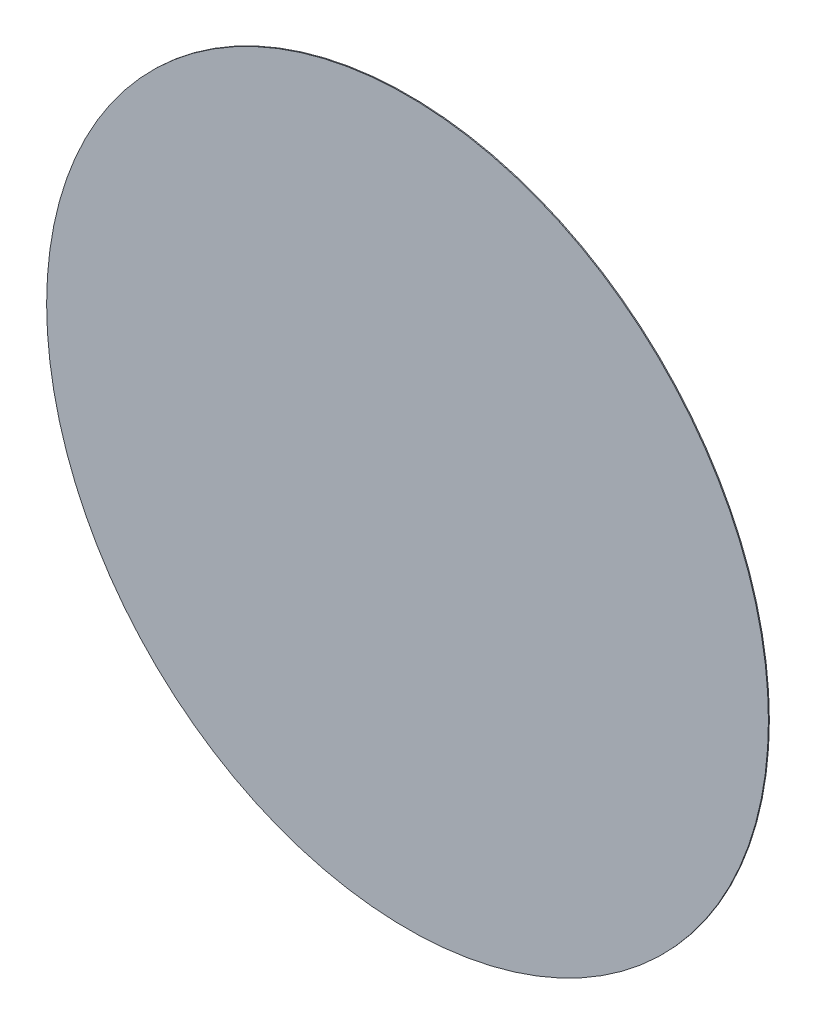
SolidWorks part; units mm, degrees
ref_plane "Front Plane" through (0, 0, 0) normal (0, 0, 1) x (1, 0, 0)
ref_plane "Top Plane" through (0, 0, 0) normal (0, 1, 0) x (1, 0, 0)
ref_plane "Right Plane" through (0, 0, 0) normal (1, 0, 0) x (0, 0, -1)
sketch "Sketch1" plane through (0, 0, 0) normal (0, 0, 1) x (1, 0, 0)
  circle A1 centre (0, 0) radius 25
  dimension "D1" = 50
extrude "Boss-Extrude1" add sketch "Sketch1" along normal blind 0.065
